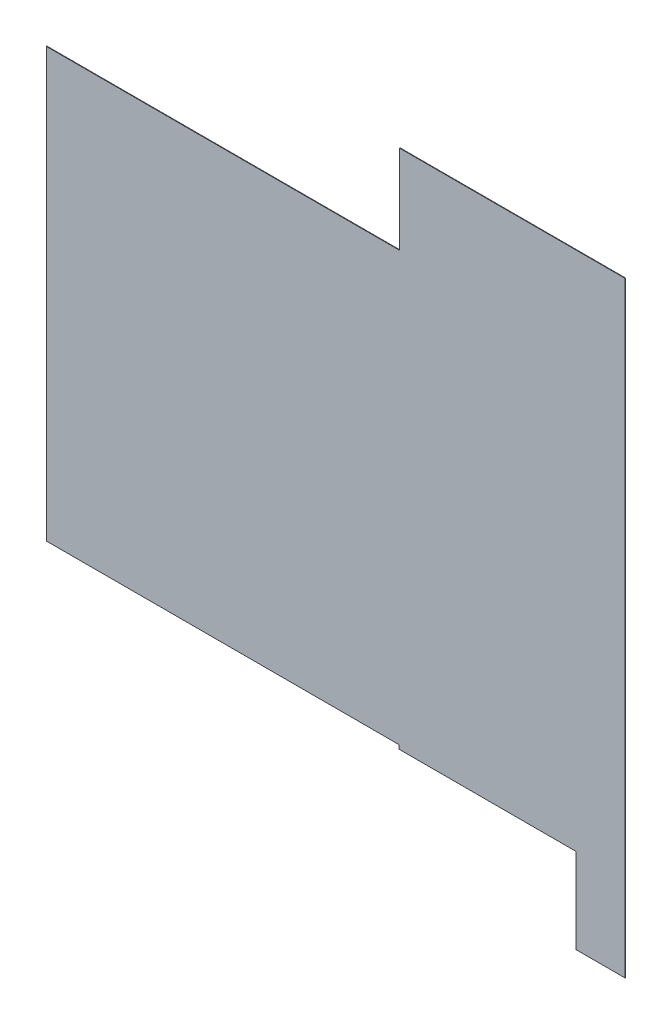
SolidWorks part; units mm, degrees
ref_plane "Front Plane" through (0, 0, 0) normal (0, 0, 1) x (1, 0, 0)
ref_plane "Top Plane" through (0, 0, 0) normal (0, 1, 0) x (1, 0, 0)
ref_plane "Right Plane" through (0, 0, 0) normal (1, 0, 0) x (0, 0, -1)
sketch "Sketch1" plane through (0, 0, 0) normal (0, 0, 1) x (1, 0, 0)
  line L1 (1242, 1506) -> (0, 1506)
  line L2 (1239.9988, 0) -> (0, 0)
  line L3 (0, 1506) -> (0, 0)
  line L9 (1672.9988, -14) -> (1672.9988, -313)
  line L10 (1672.9988, -313) -> (2035, -313)
  line L11 (2035, -313) -> (2035, 1817)
  line L12 (2035, 1817) -> (1242, 1817)
  line L13 (1242, 1817) -> (1242, 1506)
  line L17 (1672.9988, -14) -> (1239.9988, -14)
  line L18 (1239.9988, 0) -> (1239.9988, -14)
other "Pen Sketch1" parameters "D1"=69.7562, "D2"=44.2015, "D3"=1675.8242, "D4"=1144.478, "D5"=271.6371, "D6"=2110, "D7"=442.9988, "D8"=311
extrude "Boss-Extrude1" add sketch "Sketch1" along normal blind 2
extrude "Cut-Extrude2" cut sketch "Sketch3" against normal blind 330
sketch "Sketch3" plane through (-124.1121, -344, 1006.4575) normal (0, -1, 0) x (-1, 0, 0)
  line L1 (-1887.1121, 819.4575) -> (-1466.1121, 819.4575)
  line L2 (-1987.1121, 919.4575) -> (-1987.1121, 2569.4575)
  line L3 (-1887.1121, 2669.4575) -> (-1466.1121, 2669.4575)
  line L4 (-1366.1121, 919.4575) -> (-1366.1121, 2569.4575)
  arc A0 (-1466.1121, 819.4575) -> (-1366.1121, 919.4575) centre (-1466.1121, 919.4575) ccw
  arc A1 (-1887.1121, 819.4575) -> (-1987.1121, 919.4575) centre (-1887.1121, 919.4575) cw
  arc A2 (-1466.1121, 2669.4575) -> (-1366.1121, 2569.4575) centre (-1466.1121, 2569.4575) cw
  arc A3 (-1987.1121, 2569.4575) -> (-1887.1121, 2669.4575) centre (-1887.1121, 2569.4575) cw
